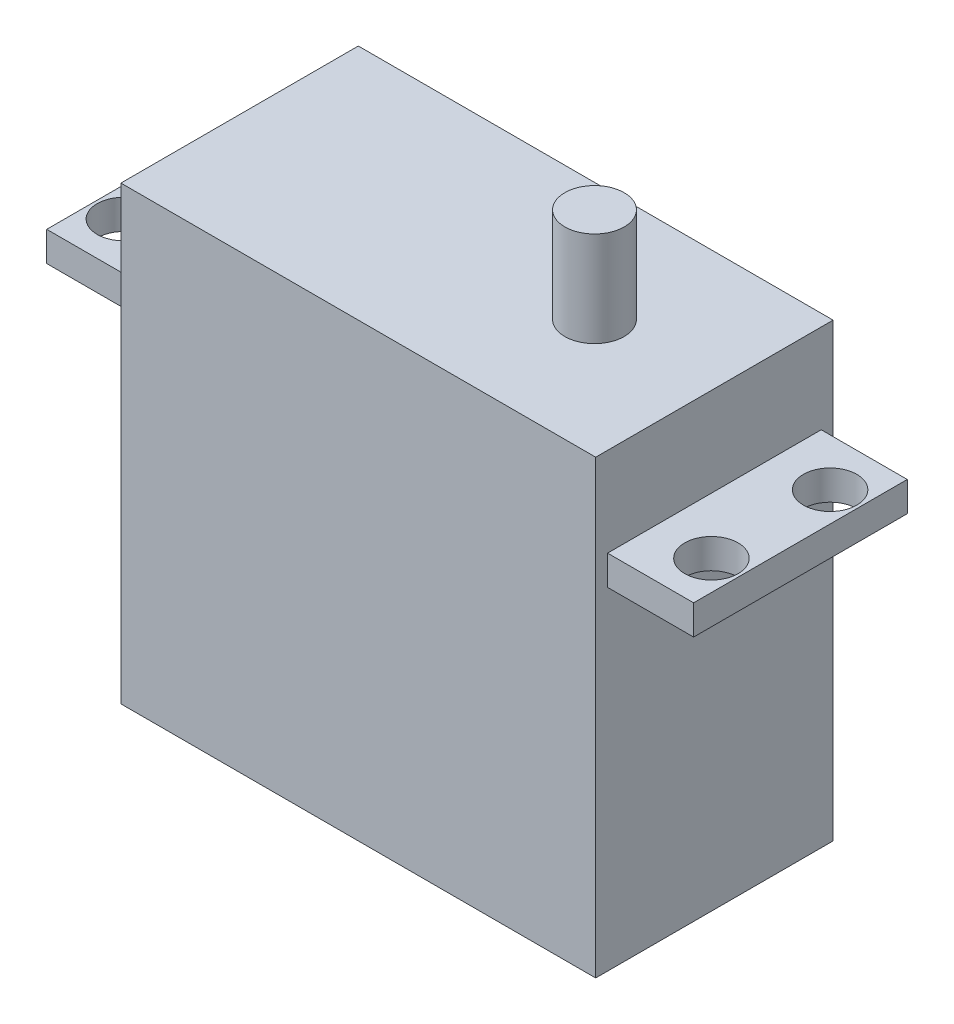
SolidWorks part; units mm, degrees
ref_plane "Front Plane" through (0, 0, 0) normal (0, 0, 1) x (1, 0, 0)
ref_plane "Top Plane" through (0, 0, 0) normal (0, 1, 0) x (1, 0, 0)
ref_plane "Right Plane" through (0, 0, 0) normal (1, 0, 0) x (0, 0, -1)
sketch "Sketch1" plane through (0, 0, 0) normal (0, 1, 0) x (1, 0, 0)
  line L1 (-29.9, 10) -> (10.1, 10)
  line L2 (-29.9, 10) -> (-29.9, -10)
  line L3 (-29.9, -10) -> (10.1, -10)
  line L4 (10.1, 10) -> (10.1, -10)
  dimension "D1" = 10.1
  dimension "D2" = 29.9
  dimension "D3" = 10
  dimension "D4" = 10
extrude "Boss-Extrude1" add sketch "Sketch1" along normal blind 10 and the other way blind 28
sketch "Sketch2" plane through (0, 10, 0) normal (0, 1, 0) x (1, 0, 0)
  circle A0 centre (0, 0) radius 2.5
  dimension "D1" = 5
extrude "Boss-Extrude2" add sketch "Sketch2" along normal blind 8
sketch "Sketch3" plane through (0, 0, 0) normal (0, 1, 0) x (1, 0, 0)
  line L0 (10.1, -10) -> (10.1, 10) construction
  line L1 (10.1, -9) -> (17.35, -9)
  line L2 (10.1, -9) -> (10.1, 9)
  line L3 (10.1, 9) -> (17.35, 9)
  line L4 (17.35, -9) -> (17.35, 9)
  point P6 (17.35, 0)
  dimension "D1" = 18
  dimension "D2" = 0
  dimension "D3" = 7.25
extrude "Boss-Extrude3" add sketch "Sketch3" along normal blind 2.5
sketch "Sketch4" plane through (0, 2.5, 0) normal (0, 1, 0) x (1, 0, 0)
  circle A0 centre (14.85, -5) radius 2.25
  circle A3 centre (14.85, 5) radius 2.25
  dimension "D1" = 4.5
  dimension "D2" = 14.85
  dimension "D3" = 5
  dimension "D4" = 4.5
  dimension "D5" = 14.85
  dimension "D6" = 5
extrude "Cut-Extrude1" cut sketch "Sketch4" against normal through all both and the other way through all
ref_plane "Plane1" through (-9.9, 0, 0) normal (-1, 0, 0) x (0, 0, 1)
mirror "Mirror1" about plane through (-9.9, 0, 0) normal (-1, 0, 0) of "Cut-Extrude1", "Boss-Extrude3"
